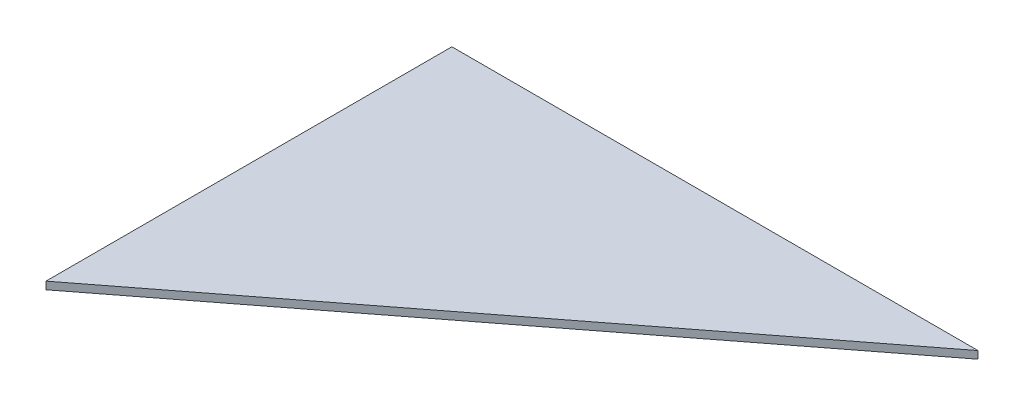
SolidWorks part; units mm, degrees
ref_plane "Front" through (0, 0, 0) normal (0, 0, 1) x (1, 0, 0)
ref_plane "Top" through (0, 0, 0) normal (0, 1, 0) x (1, 0, 0)
ref_plane "Right" through (0, 0, 0) normal (1, 0, 0) x (0, 0, -1)
sketch "Sketch1" plane through (0, 0, 0) normal (0, 1, 0) x (1, 0, 0)
  line L0 (0, 0) -> (0, 270)
  line L1 (0, 270) -> (350, 270)
  line L2 (350, 270) -> (0, 0)
  dimension "D1" = 270
  dimension "D2" = 350
  dimension "D3" = 52.352
extrude "Boss-Extrude1" add sketch "Sketch1" along normal mid plane 5
